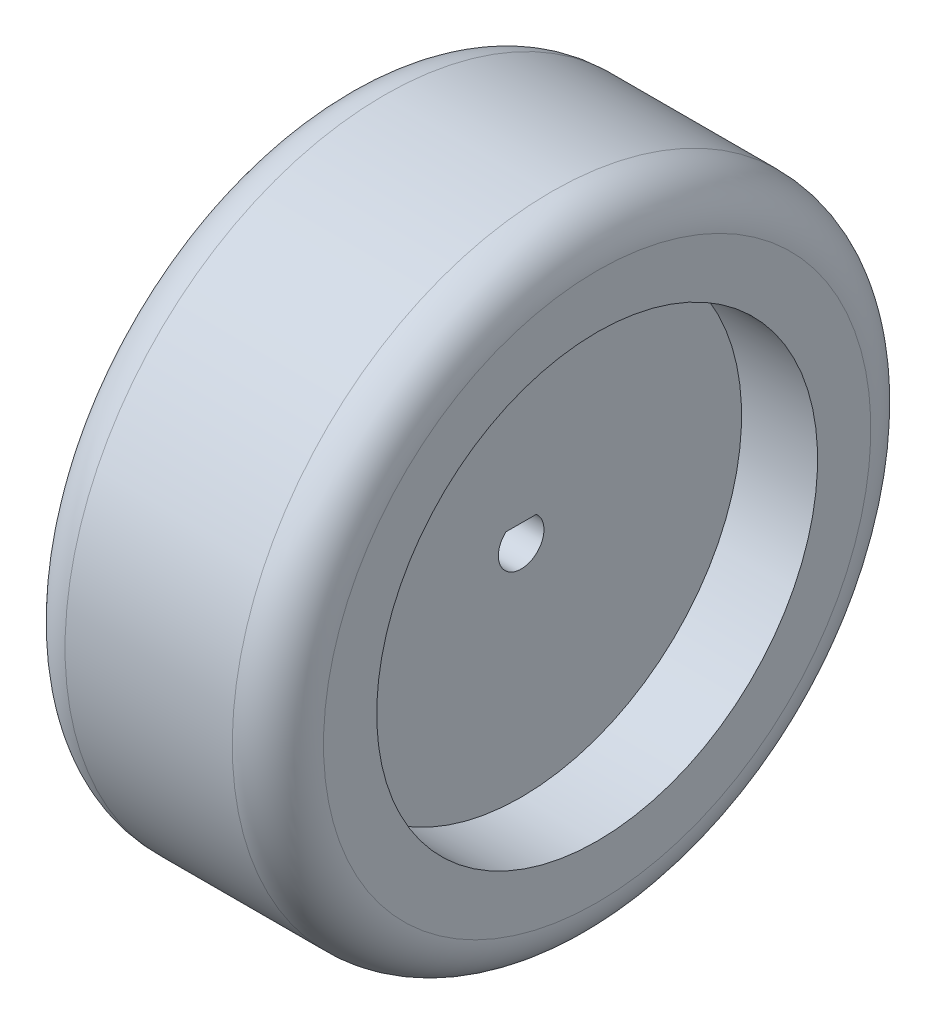
SolidWorks part; units mm, degrees
ref_plane "Plan de face" through (0, 0, 0) normal (0, 0, 1) x (1, 0, 0)
ref_plane "Plan de dessus" through (0, 0, 0) normal (0, 1, 0) x (1, 0, 0)
ref_plane "Plan de droite" through (0, 0, 0) normal (1, 0, 0) x (0, 0, -1)
sketch "Esquisse1" plane through (0, 0, 0) normal (0, 0, 1) x (1, 0, 0)
  line L0 (-17, 21) -> (0, 21)
  line L1 (0, 21) -> (0, 14.5)
  line L2 (-5, 0) -> (-9, 0)
  line L3 (-9, 0) -> (-9, 14.5)
  line L4 (-9, 14.5) -> (-17, 14.5)
  line L5 (-17, 14.5) -> (-17, 21)
  line L6 (0, 14.5) -> (-5, 14.5)
  line L7 (-5, 14.5) -> (-5, 0)
  point P3 (0, 0)
  point P4 (0, 0)
  point P9 (0, 0)
  point P13 (0, 0)
  dimension "D1" = 5
  dimension "D2" = 17
  dimension "D3" = 8
  dimension "D4" = 21
  dimension "D5" = 6.5
revolve "Révolution1" add sketch "Esquisse1" angle 360 about L2
fillet "Congé1" radius 3 2 edges at (-17, 21, 0) (0, 21, 0)
sketch "Esquisse2" plane through (-5, 0, 0) normal (1, 0, 0) x (0, 0, -1)
  line L0 (-1, 1.118) -> (1, 1.118)
  arc A0 (-1, 1.118) -> (1, 1.118) centre (0, 0) ccw
  dimension "D1" = 1.5
  dimension "D2" = 2
extrude "Enlèv. mat.-Extru.1" cut sketch "Esquisse2" against normal up to next
